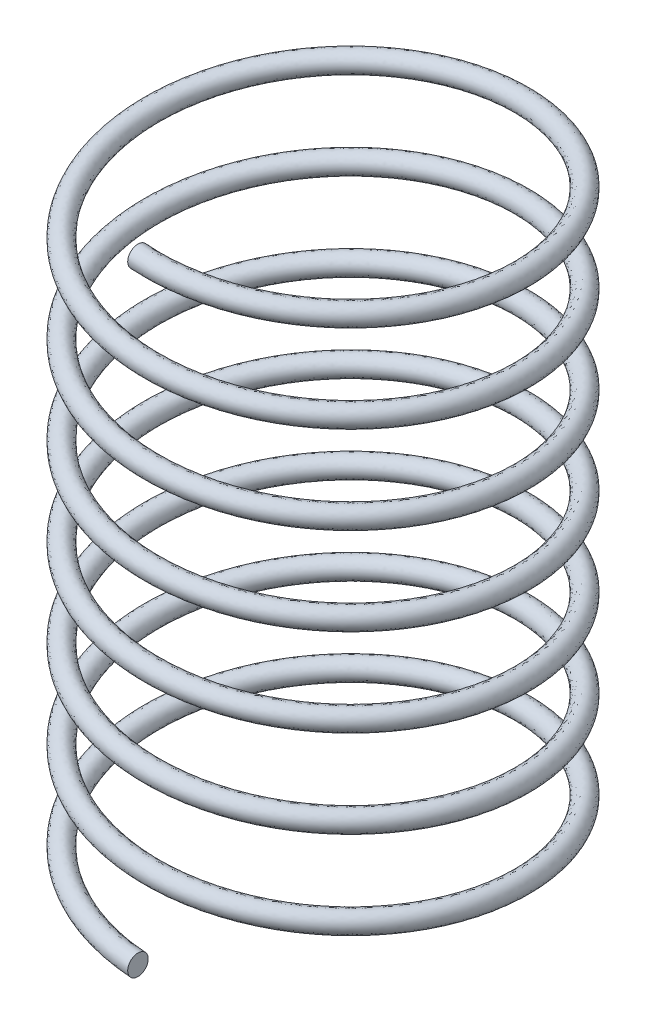
SolidWorks part; units mm, degrees
ref_plane "Front Plane" through (0, 0, 0) normal (0, 0, 1) x (1, 0, 0)
ref_plane "Top Plane" through (0, 0, 0) normal (0, 1, 0) x (1, 0, 0)
ref_plane "Right Plane" through (0, 0, 0) normal (1, 0, 0) x (0, 0, -1)
sketch "Sketch10" plane through (0, 0, 0) normal (0, 1, 0) x (1, 0, 0)
  circle A0 centre (0, 0) radius 52.7432
curve "Helix/Spiral3" pitch 25 height 175 turns 7
sketch "Sketch12" plane through (0, 0, 0) normal (1, 0, 0) x (0, 0, -1)
  circle A0 centre (-52.7432, 0) radius 2.9255
  spline S0 degree 3 poles (-52.7432, 0) (-52.7432, 0.2588) (-52.0692, 0.778) (-49.075, 1.5555) (-44.2116, 2.3333) (-37.6641, 3.1111) (-29.682, 3.8889) (-20.5694, 4.6667) (-10.6732, 5.4444) (-0.3706, 6.2222) (9.9462, 7) (19.8842, 7.7778) (29.0647, 8.5556) (37.1382, 9.3333) (43.7971, 10.1111) (48.7878, 10.8889) (51.9202, 11.6667) (53.075, 12.4444) (52.2081, 13.2222) (49.3527, 14) (44.6174, 14.7778) (38.1827, 15.5556) (30.2936, 16.3333) (21.2506, 17.1111) (11.3982, 17.8889) (1.1116, 18.6667) (-9.2173, 19.4444) (-19.1951, 20.2222) (-28.4418, 21) (-36.6051, 21.7778) (-43.3742, 22.5556) (-48.4911, 23.3333) (-51.7611, 24.1111) (-53.0594, 24.8889) (-52.3368, 25.6667) (-49.6207, 26.4444) (-45.0145, 27.2222) (-38.6938, 28) (-30.8992, 28.7778) (-21.9276, 29.5556) (-12.1209, 30.3333) (-1.8525, 31.1111) (8.4865, 31.8889) (18.5023, 32.6667) (27.8132, 33.4444) (36.0648, 34.2222) (42.9427, 35) (48.185, 35.7778) (51.5918, 36.5556) (53.0336, 37.3333) (52.4553, 38.1111) (49.879, 38.8889) (45.4029, 39.6667) (39.1973, 40.4444) (31.4988, 41.2222) (22.6004, 42) (12.8412, 42.7778) (2.593, 43.5556) (-7.7541, 44.3333) (-17.8058, 45.1111) (-27.1793, 45.8889) (-35.5175, 46.6667) (-42.5029, 47.4444) (-47.8694, 48.2222) (-51.4125, 49) (-52.9974, 49.7778) (-52.5636, 50.5556) (-50.1276, 51.3333) (-45.7823, 52.1111) (-39.6932, 52.8889) (-32.0922, 53.6667) (-23.2688, 54.4444) (-13.5591, 55.2222) (-3.3329, 56) (7.0202, 56.7778) (17.1059, 57.5556) (26.5401, 58.3333) (34.9633, 59.1111) (42.0548, 59.8889) (47.5445, 60.6667) (51.2232, 61.4444) (52.9508, 62.2222) (52.6616, 63) (50.3665, 63.7778) (46.1529, 64.5556) (40.1814, 65.3333) (32.6794, 66.1111) (23.9326, 66.8889) (14.2743, 67.6667) (4.0723, 68.4444) (-6.2849, 69.2222) (-16.4027, 70) (-25.8957, 70.7778) (-34.4023, 71.5556) (-41.5986, 72.3333) (-47.2103, 73.1111) (-51.0239, 73.8889) (-52.894, 74.6667) (-52.7493, 75.4444) (-50.5955, 76.2222) (-46.5145, 77) (-40.6617, 77.7778) (-33.2602, 78.5556) (-24.5918, 79.3333) (-14.9867, 80.1111) (-4.8108, 80.8889) (5.5484, 81.6667) (15.6962, 82.4444) (25.2462, 83.2222) (33.8346, 84) (41.1342, 84.7778) (46.867, 85.5556) (50.8147, 86.3333) (52.8268, 87.1111) (52.8268, 87.8889) (50.8147, 88.6667) (46.867, 89.4444) (41.1342, 90.2222) (33.8346, 91) (25.2462, 91.7778) (15.6962, 92.5556) (5.5484, 93.3333) (-4.8108, 94.1111) (-14.9867, 94.8889) (-24.5918, 95.6667) (-33.2602, 96.4444) (-40.6617, 97.2222) (-46.5145, 98) (-50.5955, 98.7778) (-52.7493, 99.5556) (-52.894, 100.3333) (-51.0239, 101.1111) (-47.2103, 101.8889) (-41.5986, 102.6667) (-34.4023, 103.4444) (-25.8957, 104.2222) (-16.4027, 105) (-6.2849, 105.7778) (4.0723, 106.5556) (14.2743, 107.3333) (23.9326, 108.1111) (32.6794, 108.8889) (40.1814, 109.6667) (46.1529, 110.4444) (50.3665, 111.2222) (52.6616, 112) (52.9508, 112.7778) (51.2232, 113.5556) (47.5445, 114.3333) (42.0548, 115.1111) (34.9633, 115.8889) (26.5401, 116.6667) (17.1059, 117.4444) (7.0202, 118.2222) (-3.3329, 119) (-13.5591, 119.7778) (-23.2688, 120.5556) (-32.0922, 121.3333) (-39.6932, 122.1111) (-45.7823, 122.8889) (-50.1276, 123.6667) (-52.5636, 124.4444) (-52.9974, 125.2222) (-51.4125, 126) (-47.8694, 126.7778) (-42.5029, 127.5556) (-35.5175, 128.3333) (-27.1793, 129.1111) (-17.8058, 129.8889) (-7.7541, 130.6667) (2.593, 131.4444) (12.8412, 132.2222) (22.6004, 133) (31.4988, 133.7778) (39.1973, 134.5556) (45.4029, 135.3333) (49.879, 136.1111) (52.4553, 136.8889) (53.0336, 137.6667) (51.5918, 138.4444) (48.185, 139.2222) (42.9427, 140) (36.0648, 140.7778) (27.8132, 141.5556) (18.5023, 142.3333) (8.4865, 143.1111) (-1.8525, 143.8889) (-12.1209, 144.6667) (-21.9276, 145.4444) (-30.8992, 146.2222) (-38.6938, 147) (-45.0145, 147.7778) (-49.6207, 148.5556) (-52.3368, 149.3333) (-53.0594, 150.1111) (-51.7611, 150.8889) (-48.4911, 151.6667) (-43.3742, 152.4444) (-36.6051, 153.2222) (-28.4418, 154) (-19.1951, 154.7778) (-9.2173, 155.5556) (1.1116, 156.3333) (11.3982, 157.1111) (21.2506, 157.8889) (30.2936, 158.6667) (38.1827, 159.4444) (44.6174, 160.2222) (49.3527, 161) (52.2081, 161.7778) (53.075, 162.5556) (51.9202, 163.3333) (48.7878, 164.1111) (43.7971, 164.8889) (37.1382, 165.6667) (29.0647, 166.4444) (19.8842, 167.2222) (9.9462, 168) (-0.3706, 168.7778) (-10.6732, 169.5556) (-20.5694, 170.3333) (-29.682, 171.1111) (-37.6641, 171.8889) (-44.2116, 172.6667) (-49.075, 173.4445) (-52.0692, 174.222) (-52.7432, 174.7412) (-52.7432, 175) knots 0 0 0 0 0.004444 0.008889 0.013333 0.017778 0.022222 0.026667 0.031111 0.035556 0.04 0.044444 0.048889 0.053333 0.057778 0.062222 0.066667 0.071111 0.075556 0.08 0.084444 0.088889 0.093333 0.097778 0.102222 0.106667 0.111111 0.115556 0.12 0.124444 0.128889 0.133333 0.137778 0.142222 0.146667 0.151111 0.155556 0.16 0.164444 0.168889 0.173333 0.177778 0.182222 0.186667 0.191111 0.195556 0.2 0.204444 0.208889 0.213333 0.217778 0.222222 0.226667 0.231111 0.235556 0.24 0.244444 0.248889 0.253333 0.257778 0.262222 0.266667 0.271111 0.275556 0.28 0.284444 0.288889 0.293333 0.297778 0.302222 0.306667 0.311111 0.315556 0.32 0.324444 0.328889 0.333333 0.337778 0.342222 0.346667 0.351111 0.355556 0.36 0.364444 0.368889 0.373333 0.377778 0.382222 0.386667 0.391111 0.395556 0.4 0.404444 0.408889 0.413333 0.417778 0.422222 0.426667 0.431111 0.435556 0.44 0.444444 0.448889 0.453333 0.457778 0.462222 0.466667 0.471111 0.475556 0.48 0.484444 0.488889 0.493333 0.497778 0.502222 0.506667 0.511111 0.515556 0.52 0.524444 0.528889 0.533333 0.537778 0.542222 0.546667 0.551111 0.555556 0.56 0.564444 0.568889 0.573333 0.577778 0.582222 0.586667 0.591111 0.595556 0.6 0.604444 0.608889 0.613333 0.617778 0.622222 0.626667 0.631111 0.635556 0.64 0.644444 0.648889 0.653333 0.657778 0.662222 0.666667 0.671111 0.675556 0.68 0.684444 0.688889 0.693333 0.697778 0.702222 0.706667 0.711111 0.715556 0.72 0.724444 0.728889 0.733333 0.737778 0.742222 0.746667 0.751111 0.755556 0.76 0.764444 0.768889 0.773333 0.777778 0.782222 0.786667 0.791111 0.795556 0.8 0.804444 0.808889 0.813333 0.817778 0.822222 0.826667 0.831111 0.835556 0.84 0.844444 0.848889 0.853333 0.857778 0.862222 0.866667 0.871111 0.875556 0.88 0.884444 0.888889 0.893333 0.897778 0.902222 0.906667 0.911111 0.915556 0.92 0.924444 0.928889 0.933333 0.937778 0.942222 0.946667 0.951111 0.955556 0.96 0.964444 0.968889 0.973333 0.977778 0.982222 0.986667 0.991111 0.995556 1 1 1 1 construction
sweep "Sweep3" add profiles "Sketch12" path "Helix/Spiral3"
